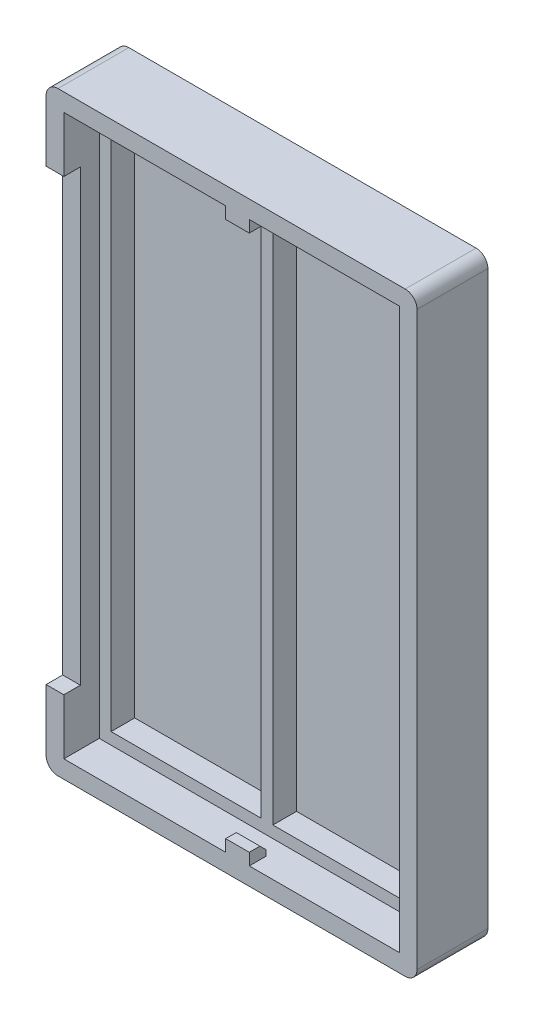
SolidWorks part; units mm, degrees
ref_plane "Front Plane" through (0, 0, 0) normal (1, 0, 0) x (0, 1, 0)
ref_plane "Top Plane" through (0, 0, 0) normal (0, 0, 1) x (0, 1, 0)
ref_plane "Right Plane" through (0, 0, 0) normal (0, 1, 0) x (-1, 0, 0)
sketch "Sketch1" plane through (0, 0, 0) normal (0, 0, 1) x (0, 1, 0)
  line L0 (-23.7, -14.2) -> (-23.7, 14.2)
  line L1 (-23.5, -14) -> (23.5, -14) construction
  line L2 (-23.5, -14) -> (-23.5, 14) construction
  line L3 (-23.5, 14) -> (23.5, 14) construction
  line L4 (23.5, -14) -> (23.5, 14) construction
  line L5 (-23.5, -14) -> (23.5, 14) construction
  line L6 (-23.5, 14) -> (23.5, -14) construction
  line L7 (-23.7, 14.2) -> (23.7, 14.2)
  line L8 (23.7, -14.2) -> (23.7, 14.2)
  line L9 (-23.7, -14.2) -> (23.7, -14.2)
  point P0 (0, 0)
  dimension "D1" = 47
  dimension "D2" = 28
  dimension "D3" = 0.2
extrude "Boss-Extrude1" add sketch "Sketch1" along normal blind 1 contours L0 L7 L8 L9
sketch "Sketch2" plane through (0, 0, 0) normal (0, 0, -1) x (1, 0, 0)
  line L0 (-15.7, 25.2) -> (-15.7, -25.2)
  line L1 (-15.7, -25.2) -> (15.7, -25.2)
  line L2 (15.7, -25.2) -> (15.7, 25.2)
  line L3 (15.7, 25.2) -> (-15.7, 25.2)
  line L4 (14.2, -23.7) -> (14.2, 23.7)
  line L5 (14.2, 23.7) -> (-14.2, 23.7)
  line L6 (-14.2, 23.7) -> (-14.2, -23.7)
  line L7 (-14.2, -23.7) -> (14.2, -23.7)
  line L8 (14.2, -23.7) -> (14.2, 23.7)
  line L9 (14.2, 23.7) -> (-14.2, 23.7)
  line L10 (-14.2, 23.7) -> (-14.2, -23.7)
  line L11 (-14.2, -23.7) -> (14.2, -23.7)
  dimension "D1" = 0
  dimension "D2" = 1.5
extrude "Boss-Extrude2" add sketch "Sketch2" against normal blind 6 separate body
sketch "Sketch3" plane through (0, 0, 1) normal (0, 0, 1) x (1, 0, 0)
  line L0 (0, 23.7) -> (0, -23.7) construction
  line L1 (14.2, 23.7) -> (-14.2, 23.7) construction
  line L2 (14.2, -23.7) -> (-14.2, -23.7) construction
  line L3 (-0.5, 22.7) -> (-0.5, -22.7)
  line L4 (0.5, 22.7) -> (0.5, -22.7)
  line L9 (0.5, 23.7) -> (0.5, -23.7) construction
  line L10 (-0.5, 23.7) -> (-0.5, -23.7) construction
  line L11 (-0.5, 22.7) -> (-13.2, 22.7)
  line L12 (0.5, -22.7) -> (13.2, -22.7)
  line L13 (13.2, -22.7) -> (13.2, 22.7)
  line L14 (13.2, 22.7) -> (-13.2, 22.7)
  line L15 (-13.2, 22.7) -> (-13.2, -22.7)
  line L16 (-13.2, -22.7) -> (13.2, -22.7)
  line L17 (13.2, -22.7) -> (13.2, 22.7)
  line L18 (13.2, 22.7) -> (0.5, 22.7)
  line L19 (-13.2, 22.7) -> (-13.2, -22.7)
  line L20 (-13.2, -22.7) -> (-0.5, -22.7)
  line L21 (14.2, -23.7) -> (14.2, 23.7)
  line L22 (14.2, 23.7) -> (-14.2, 23.7)
  line L23 (-14.2, 23.7) -> (-14.2, -23.7)
  line L24 (-14.2, -23.7) -> (14.2, -23.7)
  line L25 (14.2, -23.7) -> (14.2, 23.7)
  line L26 (14.2, 23.7) -> (-14.2, 23.7)
  line L27 (-14.2, 23.7) -> (-14.2, -23.7)
  line L28 (-14.2, -23.7) -> (14.2, -23.7)
  dimension "D1" = 0.5
  dimension "D2" = 0.5
  dimension "D3" = 1
  dimension "D4" = 0
extrude "Boss-Extrude3" add sketch "Sketch3" along normal blind 2
ref_plane "Plane1" through (0, 0, 4.6) normal (0, 0, 1) x (1, 0, 0)
sketch "Sketch4" plane through (0, 0, 4.6) normal (0, 0, 1) x (1, 0, 0)
  line L0 (0, 0) -> (27.3116, 0) construction
  line L1 (14.2, 23.7) -> (-14.2, 23.7) construction
  line L2 (-0.5, 22.7) -> (1.5, 22.7)
  line L3 (-0.5, 22.7) -> (-0.5, 23.7)
  line L4 (-0.5, 23.7) -> (1.5, 23.7)
  line L5 (1.5, 22.7) -> (1.5, 23.7)
  line L6 (1.5, -22.7) -> (1.5, -23.7)
  line L7 (-0.5, -23.7) -> (1.5, -23.7)
  line L8 (-0.5, -22.7) -> (-0.5, -23.7)
  line L9 (-0.5, -22.7) -> (1.5, -22.7)
  dimension "D1" = 2
extrude "Boss-Extrude4" add sketch "Sketch4" along normal up to surface (1.4 mm away) up to face at (0, 0, 6)
chamfer "Chamfer1" distance 0.5 angle 45 2 edges at (0.5, 22.7, 4.6) (0.5, -22.7, 4.6)
sketch "Sketch5" plane through (0, 0, 6) normal (0, 0, 1) x (1, 0, 0)
  line L0 (-14.2, 23.7) -> (-14.2, -23.7) construction
  line L1 (-9.3954, -19) -> (-19.0046, -19)
  line L2 (-9.3954, -19) -> (-9.3954, 19)
  line L3 (-9.3954, 19) -> (-19.0046, 19)
  line L4 (-19.0046, -19) -> (-19.0046, 19)
  line L5 (-9.3954, -19) -> (-19.0046, 19) construction
  line L6 (-9.3954, 19) -> (-19.0046, -19) construction
  point P0 (-14.2, 0)
  dimension "D1" = 38
extrude "Cut-Extrude1" cut sketch "Sketch5" against normal up to surface (1.4 mm away)
fillet "Fillet1" radius 1 4 edges at (-15.7, -25.2, 3) (-15.7, 25.2, 3) (15.7, 25.2, 3) (15.7, -25.2, 3)
